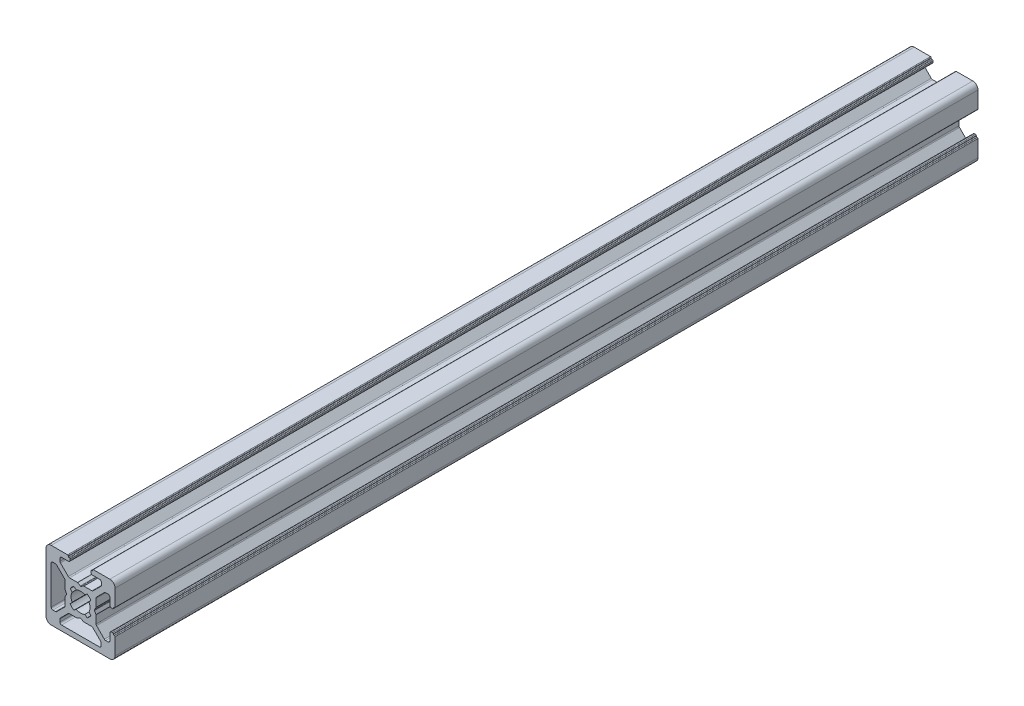
SolidWorks part; units mm, degrees
ref_plane "Front Plane" through (0, 0, 0) normal (0, 0, 1) x (1, 0, 0)
ref_plane "Top Plane" through (0, 0, 0) normal (0, 1, 0) x (1, 0, 0)
ref_plane "Right Plane" through (0, 0, 0) normal (1, 0, 0) x (0, 0, -1)
sketch "Sketch1" plane through (0, 0, 0) normal (0, 0, 1) x (1, 0, 0)
  line L0 (-8.5, -10) -> (8.5, -10)
  line L1 (-5.5, -8.5) -> (5.5, -8.5)
  line L2 (1.2582, -2.4453) -> (1.9139, -2.9896)
  line L3 (3.2322, -4.5) -> (0.9536, -4.5)
  line L4 (1.2582, 2.4453) -> (1.9139, 2.9896)
  line L5 (3.2822, 4.5) -> (1.0036, 4.5)
  line L6 (-10, -8.5) -> (-10, 8.5)
  line L7 (-8.5, -5.5) -> (-8.5, 5.5)
  line L8 (-4.6464, -3.5858) -> (-6.9142, -5.8536)
  line L9 (-7.2678, -6) -> (-8, -6)
  line L10 (-3.5858, -4.6464) -> (-5.8536, -6.9142)
  line L11 (-6, -7.2678) -> (-6, -8)
  line L12 (-2.4453, -1.2582) -> (-2.9922, -1.9099)
  line L13 (-3.2322, -4.5) -> (-0.9536, -4.5)
  line L14 (-4.5, -3.2322) -> (-4.5, -0.9536)
  line L15 (-4.4732, -0.8536) -> (-4.0381, -0.1)
  line L16 (-1.2582, -2.4453) -> (-1.9139, -2.9896)
  line L17 (0.8536, -4.4732) -> (0.1, -4.0381)
  line L18 (-0.8536, -4.4732) -> (-0.1, -4.0381)
  line L19 (-4.6464, 3.5858) -> (-6.9142, 5.8536)
  line L20 (-3.75, 10) -> (-8.5, 10)
  line L21 (-7.2678, 6) -> (-8, 6)
  line L22 (-3.5358, 4.6464) -> (-5.8036, 6.9142)
  line L23 (-2.4453, 1.2582) -> (-2.9896, 1.9139)
  line L24 (-3.1822, 4.5) -> (-0.9036, 4.5)
  line L25 (-4.5, 3.2322) -> (-4.5, 0.9536)
  line L26 (-4.4732, 0.8536) -> (-4.0381, 0.1)
  line L27 (-1.2582, 2.4453) -> (-1.9139, 2.9896)
  line L28 (0.9036, 4.4732) -> (0.15, 4.0381)
  line L29 (-0.8036, 4.4732) -> (-0.05, 4.0381)
  line L30 (-3.55, 9.7) -> (-3.55, 9.8)
  line L31 (-3.2, 9.5) -> (-3.35, 9.5)
  line L32 (-5.95, 7.2678) -> (-5.95, 8)
  line L33 (-3, 9) -> (-3, 9.3)
  line L34 (-3.5, 8.5) -> (-5.45, 8.5)
  line L35 (4.6464, -3.5858) -> (6.9142, -5.8536)
  line L36 (3.5858, -4.6464) -> (5.8536, -6.9142)
  line L37 (7.2678, -6) -> (8, -6)
  line L38 (6, -7.2678) -> (6, -8)
  line L39 (2.4453, -1.2582) -> (2.9896, -1.9139)
  line L40 (4.5, -3.2322) -> (4.5, -0.9536)
  line L41 (4.4732, -0.8536) -> (4.0381, -0.1)
  line L42 (9, -3) -> (9.3, -3)
  line L43 (9.5, -3.2) -> (9.5, -3.3)
  line L44 (8.5, -3.5) -> (8.5, -5.5)
  line L45 (9.7, -3.5) -> (9.8, -3.5)
  line L46 (10, -3.7) -> (10, -8.5)
  line L47 (3.6358, 4.6464) -> (5.9036, 6.9142)
  line L48 (4.6464, 3.5858) -> (6.9142, 5.8536)
  line L49 (4.5, 3.2322) -> (4.5, 0.9536)
  line L50 (2.4453, 1.2582) -> (2.9896, 1.9139)
  line L51 (4.4732, 0.8536) -> (4.0381, 0.1)
  line L52 (7.2678, 6) -> (8, 6)
  line L53 (9, 3) -> (9.3, 3)
  line L54 (9.5, 3.2) -> (9.5, 3.3)
  line L55 (8.5, 3.5) -> (8.5, 5.5)
  line L56 (9.7, 3.5) -> (9.8, 3.5)
  line L57 (3.7, 10) -> (8.5, 10)
  line L58 (3, 9) -> (3, 9.3)
  line L59 (3.5, 9.7) -> (3.5, 9.8)
  line L60 (3.2, 9.5) -> (3.3, 9.5)
  line L61 (3.5, 8.5) -> (5.55, 8.5)
  line L62 (6.05, 7.2678) -> (6.05, 8)
  line L63 (10, 3.7) -> (10, 8.5)
  line L64 (0, 13.2358) -> (0, -12.7247) construction
  line L65 (12.4331, 0) -> (-14.3196, 0) construction
  arc A0 (-4.0381, -0.1) -> (-4.0381, 0.1) centre (-4.2113, 0) ccw
  arc A1 (-2.4453, 1.2582) -> (-2.4453, -1.2582) centre (0, 0) ccw
  arc A2 (-8.5, -5.5) -> (-8, -6) centre (-8, -5.5) ccw
  arc A3 (-7.2678, -6) -> (-6.9142, -5.8536) centre (-7.2678, -5.5) ccw
  arc A4 (-10, -8.5) -> (-8.5, -10) centre (-8.5, -8.5) ccw
  arc A5 (-6, -8) -> (-5.5, -8.5) centre (-5.5, -8) ccw
  arc A6 (-5.8536, -6.9142) -> (-6, -7.2678) centre (-5.5, -7.2678) ccw
  arc A7 (-2.9922, -1.9099) -> (-1.9139, -2.9896) centre (0, 0) ccw
  arc A8 (-3.2322, -4.5) -> (-3.5858, -4.6464) centre (-3.2322, -5) ccw
  arc A9 (-4.4732, -0.8536) -> (-4.5, -0.9536) centre (-4.3, -0.9536) ccw
  arc A10 (-4.6464, -3.5858) -> (-4.5, -3.2322) centre (-5, -3.2322) ccw
  arc A11 (-1.2582, -2.4453) -> (1.2582, -2.4453) centre (0, 0) ccw
  arc A12 (0.1, -4.0381) -> (-0.1, -4.0381) centre (0, -4.2113) ccw
  arc A13 (-0.9536, -4.5) -> (-0.8536, -4.4732) centre (-0.9536, -4.3) ccw
  arc A14 (0.8536, -4.4732) -> (0.9536, -4.5) centre (0.9536, -4.3) ccw
  arc A15 (-8, 6) -> (-8.5, 5.5) centre (-8, 5.5) ccw
  arc A16 (-6.9142, 5.8536) -> (-7.2678, 6) centre (-7.2678, 5.5) ccw
  arc A17 (-8.5, 10) -> (-10, 8.5) centre (-8.5, 8.5) ccw
  arc A18 (-1.9139, 2.9896) -> (-2.9896, 1.9139) centre (0, 0) ccw
  arc A19 (-4.5, 0.9536) -> (-4.4732, 0.8536) centre (-4.3, 0.9536) ccw
  arc A20 (-4.5, 3.2322) -> (-4.6464, 3.5858) centre (-5, 3.2322) ccw
  arc A21 (-3.5358, 4.6464) -> (-3.1822, 4.5) centre (-3.1822, 5) ccw
  arc A22 (-0.8036, 4.4732) -> (-0.9036, 4.5) centre (-0.9036, 4.3) ccw
  arc A23 (1.0036, 4.5) -> (0.9036, 4.4732) centre (1.0036, 4.3) ccw
  arc A24 (-0.05, 4.0381) -> (0.15, 4.0381) centre (0.05, 4.2113) ccw
  arc A25 (1.2582, 2.4453) -> (-1.2582, 2.4453) centre (0, 0) ccw
  arc A26 (-3.5, 8.5) -> (-3, 9) centre (-3.5, 9) ccw
  arc A27 (-3.55, 9.7) -> (-3.35, 9.5) centre (-3.35, 9.7) ccw
  arc A28 (-3.55, 9.8) -> (-3.75, 10) centre (-3.75, 9.8) ccw
  arc A29 (-3, 9.3) -> (-3.2, 9.5) centre (-3.2, 9.3) ccw
  arc A30 (-5.95, 7.2678) -> (-5.8036, 6.9142) centre (-5.45, 7.2678) ccw
  arc A31 (-5.45, 8.5) -> (-5.95, 8) centre (-5.45, 8) ccw
  arc A32 (4.0381, 0.1) -> (4.0381, -0.1) centre (4.2113, 0) ccw
  arc A33 (2.4453, -1.2582) -> (2.4453, 1.2582) centre (0, 0) ccw
  arc A34 (10, -3.7) -> (9.8, -3.5) centre (9.8, -3.7) ccw
  arc A35 (8.5, -10) -> (10, -8.5) centre (8.5, -8.5) ccw
  arc A36 (8, -6) -> (8.5, -5.5) centre (8, -5.5) ccw
  arc A37 (5.5, -8.5) -> (6, -8) centre (5.5, -8) ccw
  arc A38 (6.9142, -5.8536) -> (7.2678, -6) centre (7.2678, -5.5) ccw
  arc A39 (6, -7.2678) -> (5.8536, -6.9142) centre (5.5, -7.2678) ccw
  arc A40 (1.9139, -2.9896) -> (2.9896, -1.9139) centre (0, 0) ccw
  arc A41 (4.5, -0.9536) -> (4.4732, -0.8536) centre (4.3, -0.9536) ccw
  arc A42 (4.5, -3.2322) -> (4.6464, -3.5858) centre (5, -3.2322) ccw
  arc A43 (3.5858, -4.6464) -> (3.2322, -4.5) centre (3.2322, -5) ccw
  arc A44 (9, -3) -> (8.5, -3.5) centre (9, -3.5) ccw
  arc A45 (9.5, -3.3) -> (9.7, -3.5) centre (9.7, -3.3) ccw
  arc A46 (9.5, -3.2) -> (9.3, -3) centre (9.3, -3.2) ccw
  arc A47 (9.8, 3.5) -> (10, 3.7) centre (9.8, 3.7) ccw
  arc A48 (10, 8.5) -> (8.5, 10) centre (8.5, 8.5) ccw
  arc A49 (8.5, 5.5) -> (8, 6) centre (8, 5.5) ccw
  arc A50 (2.9896, 1.9139) -> (1.9139, 2.9896) centre (0, 0) ccw
  arc A51 (4.4732, 0.8536) -> (4.5, 0.9536) centre (4.3, 0.9536) ccw
  arc A52 (4.6464, 3.5858) -> (4.5, 3.2322) centre (5, 3.2322) ccw
  arc A53 (3.2822, 4.5) -> (3.6358, 4.6464) centre (3.2822, 5) ccw
  arc A54 (7.2678, 6) -> (6.9142, 5.8536) centre (7.2678, 5.5) ccw
  arc A55 (8.5, 3.5) -> (9, 3) centre (9, 3.5) ccw
  arc A56 (9.3, 3) -> (9.5, 3.2) centre (9.3, 3.2) ccw
  arc A57 (9.7, 3.5) -> (9.5, 3.3) centre (9.7, 3.3) ccw
  arc A58 (6.05, 8) -> (5.55, 8.5) centre (5.55, 8) ccw
  arc A59 (3, 9) -> (3.5, 8.5) centre (3.5, 9) ccw
  arc A60 (3.3, 9.5) -> (3.5, 9.7) centre (3.3, 9.7) ccw
  arc A61 (3.7, 10) -> (3.5, 9.8) centre (3.7, 9.8) ccw
  arc A62 (3.2, 9.5) -> (3, 9.3) centre (3.2, 9.3) ccw
  arc A63 (5.9036, 6.9142) -> (6.05, 7.2678) centre (5.55, 7.2678) ccw
  dimension "D6" = 5.5
  dimension "D1" = 20
  dimension "D2" = 20
  dimension "D3" = 10
  dimension "D4" = 6
  dimension "D5" = 6
extrude "Extrude1" add sketch "Sketch1" along normal blind 250
